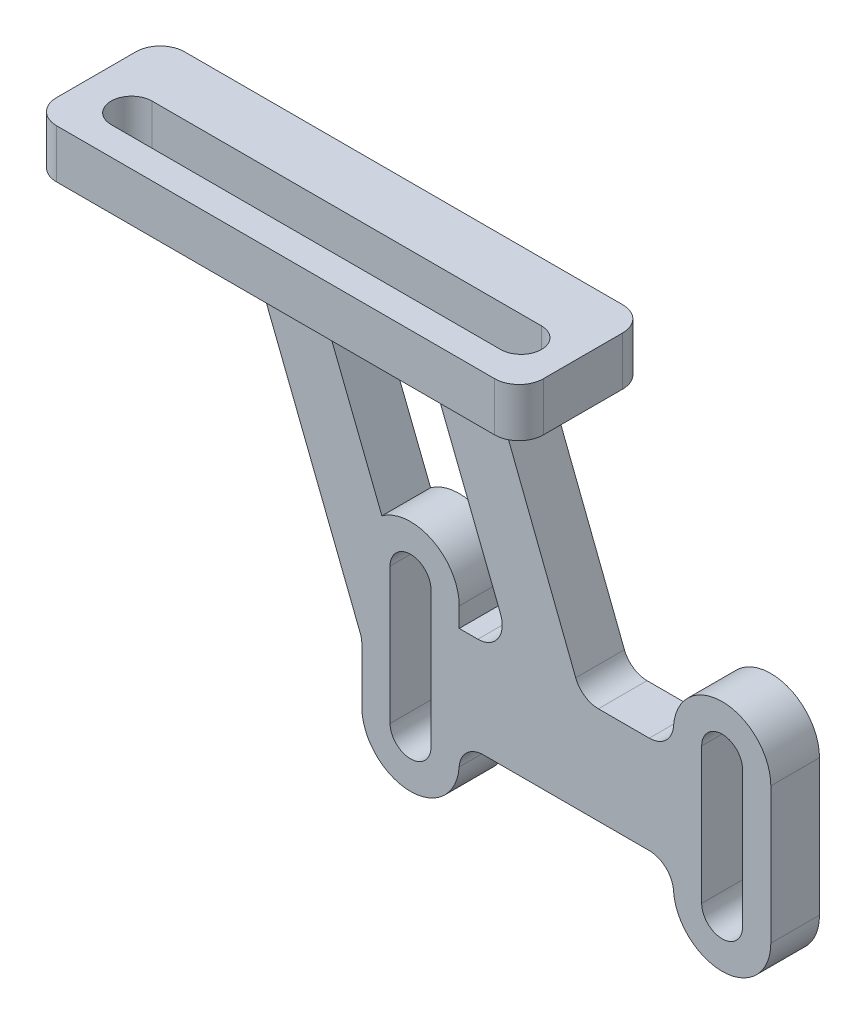
SolidWorks part; units mm, degrees
ref_plane "Front" through (0, 0, 0) normal (0, 0, 1) x (1, 0, 0)
ref_plane "Top" through (0, 0, 0) normal (0, 1, 0) x (1, 0, 0)
ref_plane "Right" through (0, 0, 0) normal (1, 0, 0) x (0, 0, -1)
sketch "Sketch1" plane through (0, 0, 0) normal (0, 1, 0) x (1, 0, 0)
  line L1 (20.5, 3.15) -> (-4.5, 3.15)
  line L2 (-4.5, -5) -> (20.5, -5)
  line L3 (-4.5, -5) -> (-4.5, 3.15)
  line L5 (20.5, -5) -> (20.5, 3.15)
  line L6 (-4.5, -5) -> (15.875, 3.15) construction
  line L7 (0.125, 3.15) -> (20.5, -5) construction
  circle A0 centre (16, 0) radius 2.1
  circle A1 centre (0, 0) radius 2.1
  point P5 (8, 0)
extrude "Boss-Extrude1" add sketch "Sketch1" along normal blind 5
sketch "Sketch3" plane through (0, 0, -3.15) normal (0, 0, -1) x (-1, 0, 0)
  line L1 (-20.5, 5) -> (4.5, 5)
  line L2 (-20.5, 5) -> (-20.5, 0)
  line L4 (4.5, 5) -> (4.5, 0)
  line L6 (4.5, 0) -> (-8.5, -33.1011)
  line L7 (-18.5, -37.1845) -> (-40.5, -37.1845)
  line L8 (-31.0834, -27.1845) -> (-40.5, -27.1845)
  line L9 (-20.5, 0) -> (-31.0834, -27.1845)
  line L10 (-6.0512, -4.8161) -> (-15.2539, -4.8161)
  line L12 (-15.2539, -4.8161) -> (-24.0925, -27.1845)
  line L13 (-24.0925, -27.1845) -> (-18.5, -27.1845)
  line L15 (-4.1055, -4.8161) -> (-6.0512, -4.8161)
  line L16 (-40.5, -37.1845) -> (-40.5, -39.1845)
  line L17 (-13.5, -39.1845) -> (-13.5, -25.1845) construction
  line L20 (-13.5, -39.1845) -> (-13.5, -25.1845) construction
  line L21 (-15.6, -39.1845) -> (-15.6, -25.1845)
  line L22 (-11.4, -39.1845) -> (-11.4, -25.1845)
  line L23 (-18.5, -27.1845) -> (-18.5, -25.1845)
  line L26 (-45.5, -25.1845) -> (-45.5, -39.1845) construction
  line L27 (-43.4, -25.1845) -> (-43.4, -39.1845)
  line L28 (-47.6, -25.1845) -> (-47.6, -39.1845)
  line L29 (-45.5, -25.1845) -> (-45.5, -39.1845) construction
  line L30 (-40.5, -25.1845) -> (-40.5, -27.1845)
  line L31 (-50.5, -25.1845) -> (-50.5, -39.1845)
  line L32 (-18.5, -39.1845) -> (-18.5, -37.1845)
  line L33 (-8.5, -39.1845) -> (-8.5, -33.1011)
  line L34 (-10.5568, -21.1426) -> (-4.1055, -4.8161)
  arc A6 (-15.6, -39.1845) -> (-11.4, -39.1845) centre (-13.5, -39.1845) ccw
  arc A7 (-11.4, -25.1845) -> (-15.6, -25.1845) centre (-13.5, -25.1845) ccw
  arc A10 (-43.4, -25.1845) -> (-47.6, -25.1845) centre (-45.5, -25.1845) ccw
  arc A11 (-47.6, -39.1845) -> (-43.4, -39.1845) centre (-45.5, -39.1845) ccw
  arc A12 (-40.5, -25.1845) -> (-50.5, -25.1845) centre (-45.5, -25.1845) ccw
  arc A13 (-50.5, -39.1845) -> (-40.5, -39.1845) centre (-45.5, -39.1845) ccw
  arc A14 (-18.5, -39.1845) -> (-8.5, -39.1845) centre (-13.5, -39.1845) ccw
  arc A15 (-10.5568, -21.1426) -> (-18.5, -25.1845) centre (-13.5, -25.1845) ccw
  point P11 (-29.5, -32.1845)
  point P31 (-13.5, -32.1845)
  point P41 (-13.5, -32.1845)
  point P45 (-45.5, -32.1845)
  point P52 (-45.5, -32.1845)
extrude "Boss-Extrude3" add sketch "Sketch3" along normal blind 5
fillet "Fillet1" radius 2.5 9 edges at (-4.5, 2.5, 5) (20.5, 2.5, 5) (31.0834, -27.1845, -5.65) (24.0925, -27.1845, -5.65) (15.2539, -4.8161, -5.65) (40.5, -27.1845, -5.65) (8.5, -33.1011, -5.65) (40.5, -37.1845, -5.65) (18.5, -37.1845, -5.65)
sketch "Sketch4" plane through (0, 5, 0) normal (0, 1, 0) x (1, 0, 0)
  line L0 (18, -5) -> (18, 8.15)
  line L1 (-4.5, 8.15) -> (20.5, 8.15) construction
  line L3 (-17.2071, -5) -> (32.7929, -5)
  line L4 (-17.2071, -5) -> (-17.2071, 8.15)
  line L5 (-17.2071, 8.15) -> (32.7929, 8.15)
  line L6 (32.7929, -5) -> (32.7929, 8.15)
  line L7 (-17.2071, -5) -> (32.7929, 8.15) construction
  line L8 (-17.2071, 8.15) -> (32.7929, -5) construction
  point P5 (7.7929, 1.575)
  circle M1 centre (0, 0) radius 2.1
  circle M2 centre (16, 0) radius 2.1
  line M3 (-4.5, 8.15) -> (-4.5, -2.5)
  arc M4 (-4.5, -2.5) -> (-2, -5) centre (-2, -2.5) ccw
  line M5 (-2, -5) -> (18, -5)
  arc M6 (18, -5) -> (20.5, -2.5) centre (18, -2.5) ccw
  line M7 (20.5, -2.5) -> (20.5, 8.15)
  line M8 (20.5, 8.15) -> (-4.5, 8.15)
extrude "Boss-Extrude4" add sketch "Sketch4" against normal blind 5 contours L3 L6 L5 M7 M6 | L0 M5 M2 M8 M3 M4 M1 | L5 L4 L3 M4 M3
sketch "Sketch5" plane through (0, 5, 0) normal (0, 1, 0) x (1, 0, 0)
  line L0 (0, 0) -> (16, 0)
  line L1 (-12, 0) -> (28, 0) construction
  line L3 (-12, 2.1) -> (28, 2.1)
  line L4 (-12, -2.1) -> (28, -2.1)
  arc A0 (-12, 2.1) -> (-12, -2.1) centre (-12, 0) ccw
  arc A1 (28, -2.1) -> (28, 2.1) centre (28, 0) ccw
  point P8 (8, 0)
extrude "Cut-Extrude1" cut sketch "Sketch5" against normal blind 5
fillet "Fillet2" radius 2.5 4 edges at (32.7929, 2.5, 5) (32.7929, 2.5, -8.15) (-17.2071, 2.5, 5) (-17.2071, 2.5, -8.15)
